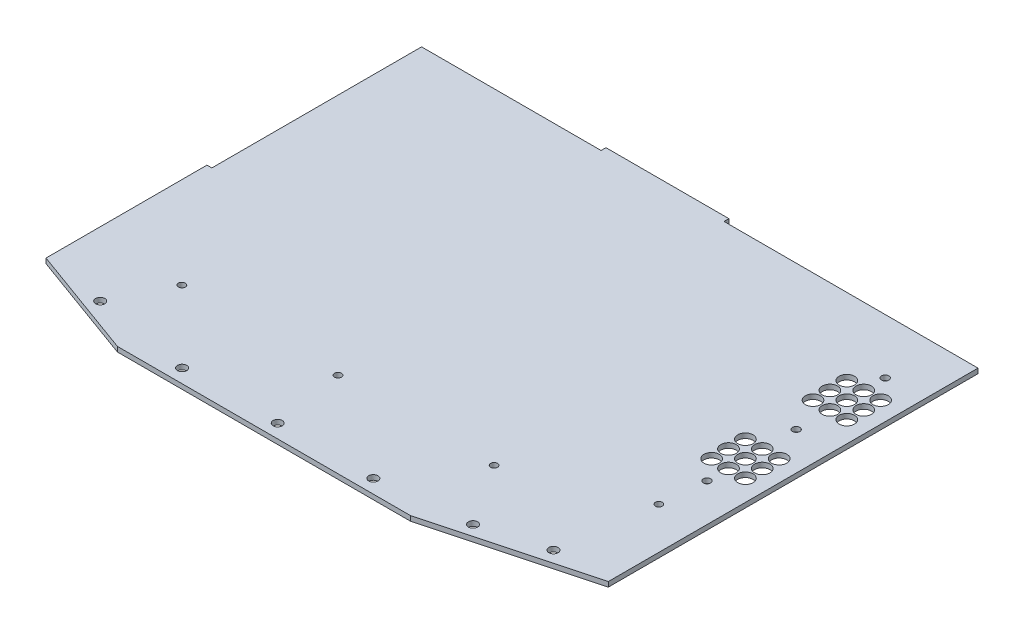
SolidWorks part; units mm, degrees
material "6061-T6 (SS)"
ref_plane "X-Y Datum" through (0, 0, 0) normal (0, 0, 1) x (1, 0, 0)
ref_plane "X-Z Datum" through (0, 0, 0) normal (0, 1, 0) x (1, 0, 0)
ref_plane "Y-Z Datum" through (0, 0, 0) normal (1, 0, 0) x (0, 0, -1)
sketch "Sketch1" plane through (0, 0, 0) normal (0, 0, 1) x (1, 0, 0)
  line L1 (-154.0561, -1.5875) -> (154.0561, -1.5875)
  line L2 (-154.0561, -1.5875) -> (-154.0561, 1.5875)
  line L3 (-154.0561, 1.5875) -> (154.0561, 1.5875)
  line L4 (154.0561, -1.5875) -> (154.0561, 1.5875)
  line L5 (-154.0561, -1.5875) -> (154.0561, 1.5875) construction
  line L6 (-154.0561, 1.5875) -> (154.0561, -1.5875) construction
  point P0 (0, 0)
  dimension "D1" = 3.175
  dimension "D2" = 308.1122
extrude "Boss-Extrude1" add sketch "Sketch1" along normal blind 267.83
sketch "Sketch3" plane through (154.0561, 0, 0) normal (1, 0, 0) x (0, 0, -1)
  line L9 (0, -1.5875) -> (0, 1.5875)
  line L10 (0, 1.5875) -> (-267.83, 1.5875)
  line L11 (-267.83, 1.5875) -> (-267.83, -1.5875)
  line L12 (-267.83, -1.5875) -> (0, -1.5875)
  line L13 (0, -1.5875) -> (0, 1.5875)
  line L14 (0, 1.5875) -> (-267.83, 1.5875)
  line L15 (-267.83, 1.5875) -> (-267.83, -1.5875)
  line L16 (-267.83, -1.5875) -> (0, -1.5875)
  dimension "D1" = 0
extrude "Boss-Extrude3" add sketch "Sketch3" along normal blind 3.175
sketch "Sketch4" plane through (0, 0, 267.83) normal (0, 0, 1) x (1, 0, 0)
  line L1 (157.2311, -1.5875) -> (208.1047, -1.5875)
  line L2 (157.2311, -1.5875) -> (157.2311, 1.5875)
  line L3 (157.2311, 1.5875) -> (208.1047, 1.5875)
  line L4 (208.1047, -1.5875) -> (208.1047, 1.5875)
  dimension "D1" = 3.175
  dimension "D2" = 50.8737
extrude "Boss-Extrude4" add sketch "Sketch4" against normal blind 267.83
sketch "Sketch6" plane through (0, 1.5875, 0) normal (0, 1, 0) x (1, 0, 0)
  line L0 (106.5047, -267.83) -> (106.5047, -228.46)
  line L1 (208.1047, -267.83) -> (-154.0561, -267.83) construction
  line L2 (208.1047, -228.46) -> (106.5047, -228.46)
  line L3 (208.1047, 0) -> (208.1047, -267.83) construction
  line L5 (106.5047, -267.83) -> (208.1047, -240.6064)
  line L6 (208.1047, -228.46) -> (208.1047, -239.4399)
  line L7 (208.1047, -239.4399) -> (208.1047, -240.6064)
  line M9 (-154.0561, -267.83) -> (208.1047, -267.83)
  line M10 (208.1047, -267.83) -> (208.1047, 0)
  dimension "D1" = 39.37
  dimension "D2" = 101.6
extrude "Cut-Extrude1" cut sketch "Sketch6" against normal through all contours L5 M9 M10
sketch "Sketch11" plane through (0, -1.5875, 0) normal (0, -1, 0) x (1, 0, 0)
  line L0 (-84.2061, 267.83) -> (-84.2061, 242.43)
  line L1 (-154.0561, 267.83) -> (106.5047, 267.83) construction
  line L3 (-154.0561, 267.83) -> (-154.0561, 0) construction
  line L4 (-154.0561, 242.43) -> (-84.2061, 267.83)
  line L5 (-154.0561, 242.43) -> (-84.2061, 242.43)
  line L6 (-154.0561, 267.83) -> (106.5047, 267.83) construction
  line M4 (-154.0561, 267.83) -> (-154.0561, 0)
  line M18 (106.5047, 267.83) -> (-154.0561, 267.83)
  dimension "D1" = 69.85
  dimension "D2" = 25.4
  dimension "D3" = 19.983
extrude "Cut-Extrude3" cut sketch "Sketch11" against normal through all contours L4 M4 M18
sketch "Sketch19" plane through (0, 1.5875, 0) normal (0, 1, 0) x (1, 0, 0)
  line L0 (208.1047, 0) -> (208.1047, -240.6064) construction
  line L1 (208.1047, 0) -> (-154.0561, 0) construction
  line L3 (164.1047, -82.5) -> (204.1047, -82.5)
  line L4 (164.1047, -82.5) -> (164.1047, -42.5)
  line L5 (164.1047, -42.5) -> (204.1047, -42.5)
  line L6 (204.1047, -82.5) -> (204.1047, -42.5)
  line L7 (164.1047, -82.5) -> (204.1047, -42.5) construction
  line L8 (164.1047, -42.5) -> (204.1047, -82.5) construction
  circle A0 centre (172.4867, -49.7748) radius 5
  dimension "D5" = 10
  dimension "D6" = 7.2748
  dimension "D1" = 40
  dimension "D2" = 40
  dimension "D3" = 42.5
  dimension "D4" = 8.382
  dimension "D7" = 4
extrude "Cut-Extrude5" cut sketch "Sketch19" against normal through all contours A0
pattern_linear "LPattern1" count 3 spacing 11 along (1, 0, 0) of "Cut-Extrude5"
pattern_linear "LPattern2" count 3 spacing 11 along (0, 0, 1) of "LPattern1", "Cut-Extrude5"
pattern_linear "LPattern3" count 2 spacing 66 along (0, 0, 1) of "LPattern2", "Cut-Extrude5", "LPattern1"
sketch "Sketch21" plane through (-154.0561, 0, 0) normal (-1, 0, 0) x (0, 0, 1)
  line L6 (242.43, -1.5875) -> (0, -1.5875) construction
  line L7 (242.43, 1.5875) -> (136.4956, 1.5875)
  line L8 (242.43, 1.5875) -> (242.43, -1.5875)
  line L9 (242.43, -1.5875) -> (136.4956, -1.5875)
  line L10 (136.4956, 1.5875) -> (136.4956, -1.5875)
  dimension "D1" = 105.9344
extrude "Boss-Extrude5" add sketch "Sketch21" along normal blind 3.175
sketch "Sketch27" plane through (0, 1.5875, 0) normal (0, 1, 0) x (1, 0, 0)
  line L2 (-84.2061, -267.83) -> (-154.0561, -242.43)
  line L3 (-154.0561, -242.43) -> (-157.2311, -241.2755)
extrude "Cut-Extrude9" cut sketch "Sketch27" against normal through all and the other way through all
sketch "Sketch32" plane through (0, 1.5875, 0) normal (0, 1, 0) x (1, 0, 0)
  circle A6 centre (172.5443, -240.7613) radius 3
  circle A7 centre (131.9043, -252.4453) radius 3
  circle A8 centre (73.4843, -258.94) radius 3
  circle A9 centre (11.2543, -258.94) radius 3
  circle A10 centre (-50.9757, -258.94) radius 3
  circle A11 centre (-115.3206, -247.9154) radius 3
extrude "Cut-Extrude11" cut sketch "Sketch32" against normal blind 80.645 and the other way through all
sketch "Sketch33" plane through (0, 1.5875, 0) normal (0, 1, 0) x (1, 0, 0)
  point P0 (180.965, -180.586)
  point P1 (105.4291, -212.285)
  point P3 (3.8291, -212.285)
  point P5 (-97.7709, -212.285)
hole_wizard "M4 Clearance Hole1" positions "Sketch33" profile "Sketch34" hole size "M4" standard "ANSI Metric" end condition through all
sketch "Sketch34" plane through (180.965, 1.5875, 180.586) normal (1, 0, 0) x (0, 0, 1)
  line L0 (0, 0) -> (0, 3.175)
  line L1 (0, 3.175) -> (2.25, 3.175)
  line L2 (2.25, 3.175) -> (2.25, 0)
  line L5 (2.25, 0) -> (0, 0)
  line L11 (0, -6.35) -> (0, 107.95) construction
  dimension "Thru Hole Dia." = 4.5
  dimension "Thru Hole Depth" = 3.175
sketch "Sketch35" plane through (0, 0, 0) normal (0, 0, -1) x (-1, 0, 0)
  line L0 (37.216, -1.576) -> (37.216, 1.599) construction
  line L1 (-42.784, -1.576) -> (-42.784, 1.599) construction
  line L2 (-42.784, -1.576) -> (37.216, -1.576) construction
  line L3 (37.216, -1.576) -> (37.216, 1.599)
  line L4 (-42.784, -1.576) -> (-42.784, 1.599)
  line L5 (-42.784, -1.576) -> (37.216, -1.576)
  line L6 (-208.1047, 1.5875) -> (154.0561, 1.5875) construction
  line L7 (-208.1047, 1.5875) -> (154.0561, 1.5875)
  line M1 (154.0561, 1.5875) -> (-208.1047, 1.5875)
extrude "Boss-Extrude6" add sketch "Sketch35" along normal blind 3.175 contours L4 L5 L3 M1
sketch "Sketch36" plane through (0, 1.5875, 0) normal (0, 1, 0) x (1, 0, 0)
  circle A0 centre (183.4867, -35.7748) radius 2.4 construction
  circle A1 centre (183.4867, -35.7748) radius 2.4
extrude "Cut-Extrude12" cut sketch "Sketch36" against normal through all both and the other way through all
pattern_linear "LPattern4" count 3 spacing 58 along (0, 0, 1) of "Cut-Extrude12"
